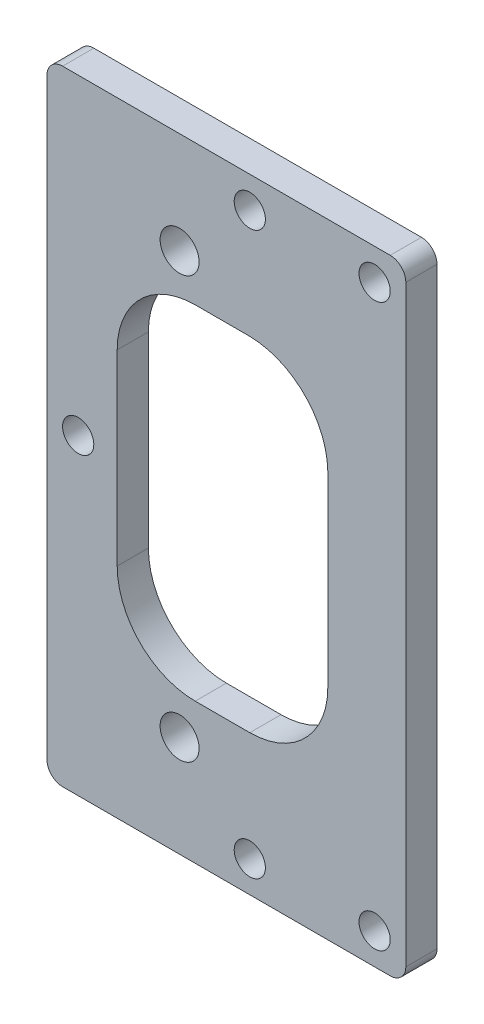
SolidWorks part; units mm, degrees
material "自訂玻璃纖維"
ref_plane "前基準面" through (0, 0, 0) normal (0, 0, 1) x (1, 0, 0)
ref_plane "上基準面" through (0, 0, 0) normal (0, 1, 0) x (1, 0, 0)
ref_plane "右基準面" through (0, 0, 0) normal (1, 0, 0) x (0, 0, -1)
sketch "草圖1" plane through (0, 0, 0) normal (0, 0, 1) x (1, 0, 0)
  line L0 (15.2838, 10.1625) -> (-25.7162, 10.1625)
  line L1 (15.2838, 10.1625) -> (15.2838, -29.8375)
  line L2 (-25.7162, -29.8375) -> (15.2838, -29.8375)
  line L12 (-25.7162, 10.1625) -> (-25.7162, -29.8375)
  circle A0 centre (-17.2162, 3.6625) radius 1.25
  circle A1 centre (-17.2162, -23.3375) radius 1.25
  circle A2 centre (12.7838, -23.3375) radius 1.25
  circle A3 centre (12.7838, 3.6625) radius 1.25
  circle A4 centre (-23.7162, -9.8375) radius 1
  point P4 (-25.7162, -9.8375)
  dimension "D7" = 6.5
  dimension "D8" = 27
  dimension "D9" = 27
  dimension "D10" = 0
  dimension "D12" = 2
  dimension "D13" = 2
  dimension "D4" = 2.5
  dimension "D5" = 30
  dimension "D3" = 6.5
  dimension "D6" = 6.5
  dimension "D2" = 2.5
extrude "填料-伸長1" add sketch "草圖1" along normal blind 2
sketch "草圖4" plane through (0, 0, 0) normal (0, 0, -1) x (-1, 0, 0)
  line L0 (-15.2838, 1.1625) -> (2.7162, 1.1625)
  line L1 (-15.2838, -29.8375) -> (-15.2838, 10.1625) construction
  line L2 (2.7162, 1.1625) -> (2.7162, -20.8375)
  line L3 (2.7162, -20.8375) -> (-15.2838, -20.8375)
  line L4 (-15.2838, -20.8375) -> (-15.2838, 1.1625)
  circle A0 centre (-12.7838, 3.6625) radius 1.25 construction
  circle A1 centre (-12.7838, -23.3375) radius 1.25 construction
  dimension "D1" = 2.5
  dimension "D2" = 2.5
  dimension "D3" = 18
extrude "除料-伸長1" cut sketch "草圖4" against normal blind 2
fillet "圓角2" radius 2.5 2 edges at (15.2838, -20.8375, 1) (15.2838, 1.1625, 1)
fillet "圓角3" radius 5 2 edges at (-2.7162, -20.8375, 1) (-2.7162, 1.1625, 1)
sketch "草圖5" plane through (0, 0, 0) normal (0, 0, -1) x (-1, 0, 0)
  line L0 (7.7162, -3.8375) -> (7.7162, -15.8375)
  line L1 (2.7162, -15.8375) -> (2.7162, -3.8375) construction
  line L2 (12.7162, 1.1625) -> (16.2162, 1.1625)
  line L3 (21.2162, -3.8375) -> (21.2162, -15.8375)
  line L4 (16.2162, -20.8375) -> (12.7162, -20.8375)
  circle A0 centre (17.2162, 3.6625) radius 1.25 construction
  circle A1 centre (17.2162, -23.3375) radius 1.25 construction
  circle A2 centre (23.7162, -9.8375) radius 1 construction
  arc A3 (7.7162, -3.8375) -> (12.7162, 1.1625) centre (12.7975, -3.9188) cw
  arc A4 (7.7162, -15.8375) -> (12.7162, -20.8375) centre (12.7162, -15.8375) ccw
  arc A5 (16.2162, 1.1625) -> (21.2162, -3.8375) centre (16.2162, -3.8375) cw
  arc A6 (21.2162, -15.8375) -> (16.2162, -20.8375) centre (16.2162, -15.8375) cw
  dimension "D7" = 5
  dimension "D8" = 5
  dimension "D1" = 5
  dimension "D2" = 2.5
  dimension "D3" = 2.5
  dimension "D4" = 2.5
  dimension "D5" = 5
  dimension "D6" = 5
extrude "除料-伸長2" cut sketch "草圖5" against normal blind 2
fillet "圓角4" radius 1 4 edges at (15.2838, -29.8375, 1) (-25.7162, -29.8375, 1) (-25.7162, 10.1625, 1) (15.2838, 10.1625, 1)
sketch "草圖6" plane through (0, 0, 0) normal (0, 0, -1) x (-1, 0, 0)
  line L1 (2.7162, -3.8375) -> (-15.2838, -3.8375)
  line L2 (2.7162, -3.8375) -> (2.7162, 10.1625)
  line L3 (2.7162, 10.1625) -> (-15.2838, 10.1625)
  line L4 (-15.2838, -3.8375) -> (-15.2838, 10.1625)
  line L5 (2.7162, -15.8375) -> (-15.2838, -15.8375)
  line L6 (2.7162, -15.8375) -> (2.7162, -29.8375)
  line L7 (2.7162, -29.8375) -> (-15.2838, -29.8375)
  line L8 (-15.2838, -15.8375) -> (-15.2838, -29.8375)
extrude "除料-伸長3" cut sketch "草圖6" against normal blind 10
fillet "圓角5" radius 1 2 edges at (-2.7162, -29.8375, 1) (-2.7162, 10.1625, 1)
sketch "草圖7" plane through (0, 0, 0) normal (0, 0, -1) x (-1, 0, 0)
  line L0 (24.7162, -29.8375) -> (3.7162, -29.8375) construction
  line L2 (2.7162, -28.8375) -> (2.7162, 9.1625) construction
  circle A0 centre (4.7162, -27.8375) radius 1
  circle A1 centre (12.7162, -27.8375) radius 1
  circle A2 centre (12.7162, 8.1625) radius 1
  circle A3 centre (4.7162, 8.1625) radius 1
  dimension "D1" = 2
  dimension "D2" = 2
  dimension "D3" = 8
  dimension "D4" = 2
  dimension "D5" = 2
extrude "除料-伸長4" cut sketch "草圖7" against normal blind 10
